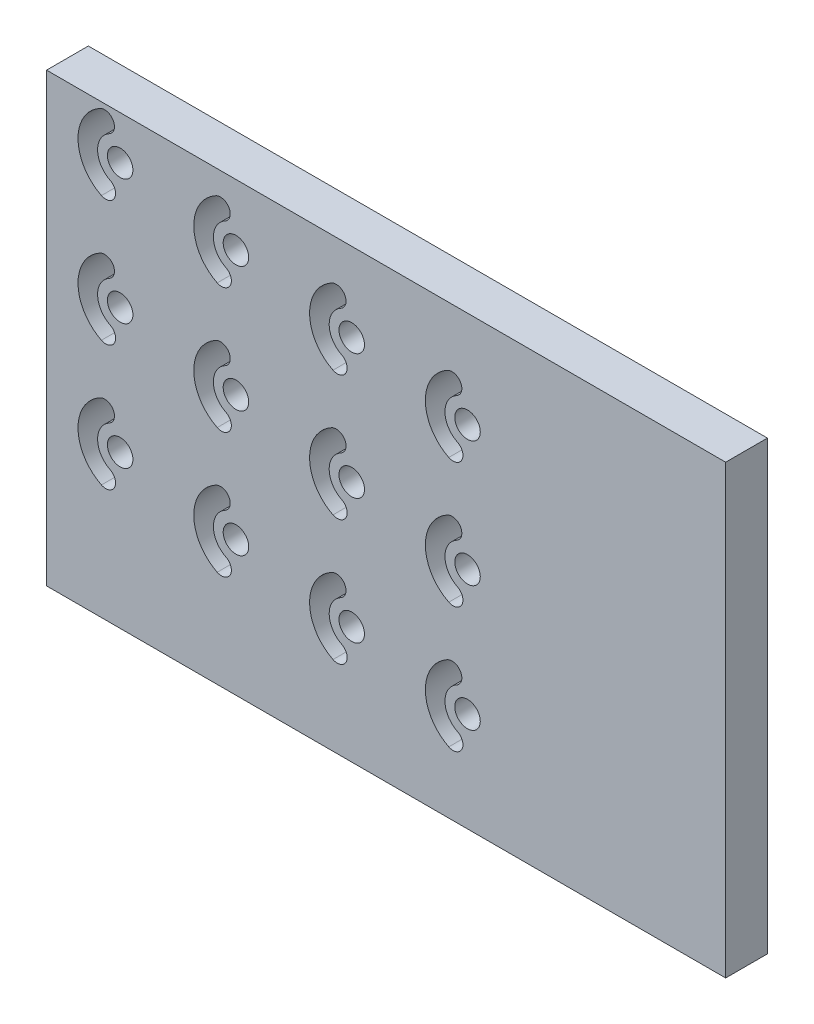
SolidWorks part; units mm, degrees
ref_plane "Спереди" through (0, 0, 0) normal (0, 0, 1) x (1, 0, 0)
ref_plane "Сверху" through (0, 0, 0) normal (0, 1, 0) x (1, 0, 0)
ref_plane "Справа" through (0, 0, 0) normal (1, 0, 0) x (0, 0, -1)
sketch "Эскиз1_fr" plane through (0, 0, 0) normal (0, 0, 1) x (1, 0, 0)
  line L0 (-25.5436, 31.4987) -> (2.1788, 27.2583) construction
  line L1 (-39.7207, 48.8394) -> (122.8713, 48.8394)
  line L2 (-39.7207, 48.8394) -> (-39.7207, -58.1127)
  line L3 (-39.7207, -58.1127) -> (122.8713, -58.1127)
  line L4 (122.8713, 48.8394) -> (122.8713, -58.1127)
  line L5 (-25.5436, 31.4987) -> (-25.5436, 1.4987) construction
  arc A0 (-25.5436, 31.4987) -> (-25.8107, 45.2386) centre (-22.1014, 38.4381) cw construction
  arc A1 (-26.9341, 47.2982) -> (-26.5862, 29.397) centre (-22.1014, 38.4381) ccw
  arc A2 (-24.6873, 43.179) -> (-24.5011, 33.6004) centre (-22.1014, 38.4381) ccw
  arc A3 (-24.6873, 43.179) -> (-26.9341, 47.2982) centre (-25.8107, 45.2386) ccw
  arc A4 (-26.5862, 29.397) -> (-24.5011, 33.6004) centre (-25.5436, 31.4987) ccw
  circle A5 centre (-22.1014, 38.4381) radius 3.0529
  circle A6 centre (5.6211, 34.1977) radius 3.0529
  arc A7 (2.1788, 27.2583) -> (1.9118, 40.9982) centre (5.6211, 34.1977) cw construction
  arc A8 (0.7884, 43.0578) -> (1.1363, 25.1566) centre (5.6211, 34.1977) ccw
  arc A9 (3.0352, 38.9386) -> (3.2214, 29.36) centre (5.6211, 34.1977) ccw
  arc A10 (3.0352, 38.9386) -> (0.7884, 43.0578) centre (1.9118, 40.9982) ccw
  arc A11 (1.1363, 25.1566) -> (3.2214, 29.36) centre (2.1788, 27.2583) ccw
  circle A12 centre (33.3436, 29.9573) radius 3.0529
  arc A13 (29.9013, 23.0179) -> (29.6343, 36.7578) centre (33.3436, 29.9573) cw construction
  arc A14 (28.5108, 38.8174) -> (28.8588, 20.9162) centre (33.3436, 29.9573) ccw
  arc A15 (30.7577, 34.6982) -> (30.9438, 25.1196) centre (33.3436, 29.9573) ccw
  arc A16 (30.7577, 34.6982) -> (28.5108, 38.8174) centre (29.6343, 36.7578) ccw
  arc A17 (28.8588, 20.9162) -> (30.9438, 25.1196) centre (29.9013, 23.0179) ccw
  circle A18 centre (61.066, 25.7169) radius 3.0529
  arc A19 (57.6238, 18.7775) -> (57.3567, 32.5174) centre (61.066, 25.7169) cw construction
  arc A20 (56.2333, 34.577) -> (56.5813, 16.6758) centre (61.066, 25.7169) ccw
  arc A21 (58.4801, 30.4578) -> (58.6663, 20.8792) centre (61.066, 25.7169) ccw
  arc A22 (58.4801, 30.4578) -> (56.2333, 34.577) centre (57.3567, 32.5174) ccw
  arc A23 (56.5813, 16.6758) -> (58.6663, 20.8792) centre (57.6238, 18.7775) ccw
  circle A24 centre (5.6211, 4.1977) radius 3.0529
  arc A25 (2.1788, -2.7417) -> (1.9118, 10.9982) centre (5.6211, 4.1977) cw construction
  arc A26 (0.7884, 13.0578) -> (1.1363, -4.8434) centre (5.6211, 4.1977) ccw
  arc A27 (3.0352, 8.9386) -> (3.2214, -0.64) centre (5.6211, 4.1977) ccw
  arc A28 (3.0352, 8.9386) -> (0.7884, 13.0578) centre (1.9118, 10.9982) ccw
  arc A29 (1.1363, -4.8434) -> (3.2214, -0.64) centre (2.1788, -2.7417) ccw
  circle A30 centre (33.3436, -0.0427) radius 3.0529
  arc A31 (29.9013, -6.9821) -> (29.6343, 6.7578) centre (33.3436, -0.0427) cw construction
  arc A32 (28.5108, 8.8174) -> (28.8588, -9.0838) centre (33.3436, -0.0427) ccw
  arc A33 (30.7577, 4.6982) -> (30.9438, -4.8804) centre (33.3436, -0.0427) ccw
  arc A34 (30.7577, 4.6982) -> (28.5108, 8.8174) centre (29.6343, 6.7578) ccw
  arc A35 (28.8588, -9.0838) -> (30.9438, -4.8804) centre (29.9013, -6.9821) ccw
  circle A36 centre (61.066, -4.2831) radius 3.0529
  arc A37 (57.6238, -11.2225) -> (57.3567, 2.5174) centre (61.066, -4.2831) cw construction
  arc A38 (56.2333, 4.577) -> (56.5813, -13.3242) centre (61.066, -4.2831) ccw
  arc A39 (58.4801, 0.4578) -> (58.6663, -9.1208) centre (61.066, -4.2831) ccw
  arc A40 (58.4801, 0.4578) -> (56.2333, 4.577) centre (57.3567, 2.5174) ccw
  arc A41 (56.5813, -13.3242) -> (58.6663, -9.1208) centre (57.6238, -11.2225) ccw
  circle A42 centre (5.6211, -25.8023) radius 3.0529
  arc A43 (2.1788, -32.7417) -> (1.9118, -19.0018) centre (5.6211, -25.8023) cw construction
  arc A44 (0.7884, -16.9422) -> (1.1363, -34.8434) centre (5.6211, -25.8023) ccw
  arc A45 (3.0352, -21.0614) -> (3.2214, -30.64) centre (5.6211, -25.8023) ccw
  arc A46 (3.0352, -21.0614) -> (0.7884, -16.9422) centre (1.9118, -19.0018) ccw
  arc A47 (1.1363, -34.8434) -> (3.2214, -30.64) centre (2.1788, -32.7417) ccw
  circle A48 centre (33.3436, -30.0427) radius 3.0529
  arc A49 (29.9013, -36.9821) -> (29.6343, -23.2422) centre (33.3436, -30.0427) cw construction
  arc A50 (28.5108, -21.1826) -> (28.8588, -39.0838) centre (33.3436, -30.0427) ccw
  arc A51 (30.7577, -25.3018) -> (30.9438, -34.8804) centre (33.3436, -30.0427) ccw
  arc A52 (30.7577, -25.3018) -> (28.5108, -21.1826) centre (29.6343, -23.2422) ccw
  arc A53 (28.8588, -39.0838) -> (30.9438, -34.8804) centre (29.9013, -36.9821) ccw
  circle A54 centre (61.066, -34.2831) radius 3.0529
  arc A55 (57.6238, -41.2225) -> (57.3567, -27.4826) centre (61.066, -34.2831) cw construction
  arc A56 (56.2333, -25.423) -> (56.5813, -43.3242) centre (61.066, -34.2831) ccw
  arc A57 (58.4801, -29.5422) -> (58.6663, -39.1208) centre (61.066, -34.2831) ccw
  arc A58 (58.4801, -29.5422) -> (56.2333, -25.423) centre (57.3567, -27.4826) ccw
  arc A59 (56.5813, -43.3242) -> (58.6663, -39.1208) centre (57.6238, -41.2225) ccw
  circle A60 centre (-22.1014, 8.4381) radius 3.0529
  arc A61 (-25.5436, 1.4987) -> (-25.8107, 15.2386) centre (-22.1014, 8.4381) cw construction
  arc A62 (-26.9341, 17.2982) -> (-26.5862, -0.603) centre (-22.1014, 8.4381) ccw
  arc A63 (-24.6873, 13.179) -> (-24.5011, 3.6004) centre (-22.1014, 8.4381) ccw
  arc A64 (-24.6873, 13.179) -> (-26.9341, 17.2982) centre (-25.8107, 15.2386) ccw
  arc A65 (-26.5862, -0.603) -> (-24.5011, 3.6004) centre (-25.5436, 1.4987) ccw
  circle A66 centre (-22.1014, -21.5619) radius 3.0529
  arc A67 (-25.5436, -28.5013) -> (-25.8107, -14.7614) centre (-22.1014, -21.5619) cw construction
  arc A68 (-26.9341, -12.7018) -> (-26.5862, -30.603) centre (-22.1014, -21.5619) ccw
  arc A69 (-24.6873, -16.821) -> (-24.5011, -26.3996) centre (-22.1014, -21.5619) ccw
  arc A70 (-24.6873, -16.821) -> (-26.9341, -12.7018) centre (-25.8107, -14.7614) ccw
  arc A71 (-26.5862, -30.603) -> (-24.5011, -26.3996) centre (-25.5436, -28.5013) ccw
  point P7 (-29.8462, 38.2876)
  point P19 (-2.1237, 34.0472)
  point P29 (25.5988, 29.8068)
  point P39 (53.3212, 25.5664)
  point P49 (-2.1237, 4.0472)
  point P59 (25.5988, -0.1932)
  point P69 (53.3212, -4.4336)
  point P79 (-2.1237, -25.9528)
  point P89 (25.5988, -30.1932)
  point P99 (53.3212, -34.4336)
  point P109 (-29.8462, 8.2876)
  point P119 (-29.8462, -21.7124)
  dimension "D1" = 4
  dimension "D2" = 28.0449
  dimension "D3" = 30
  dimension "D5" = 81.304
  dimension "D4" = 3
extrude "Бобышка-Вытянуть1" add sketch "Эскиз1_fr" along normal blind 10
